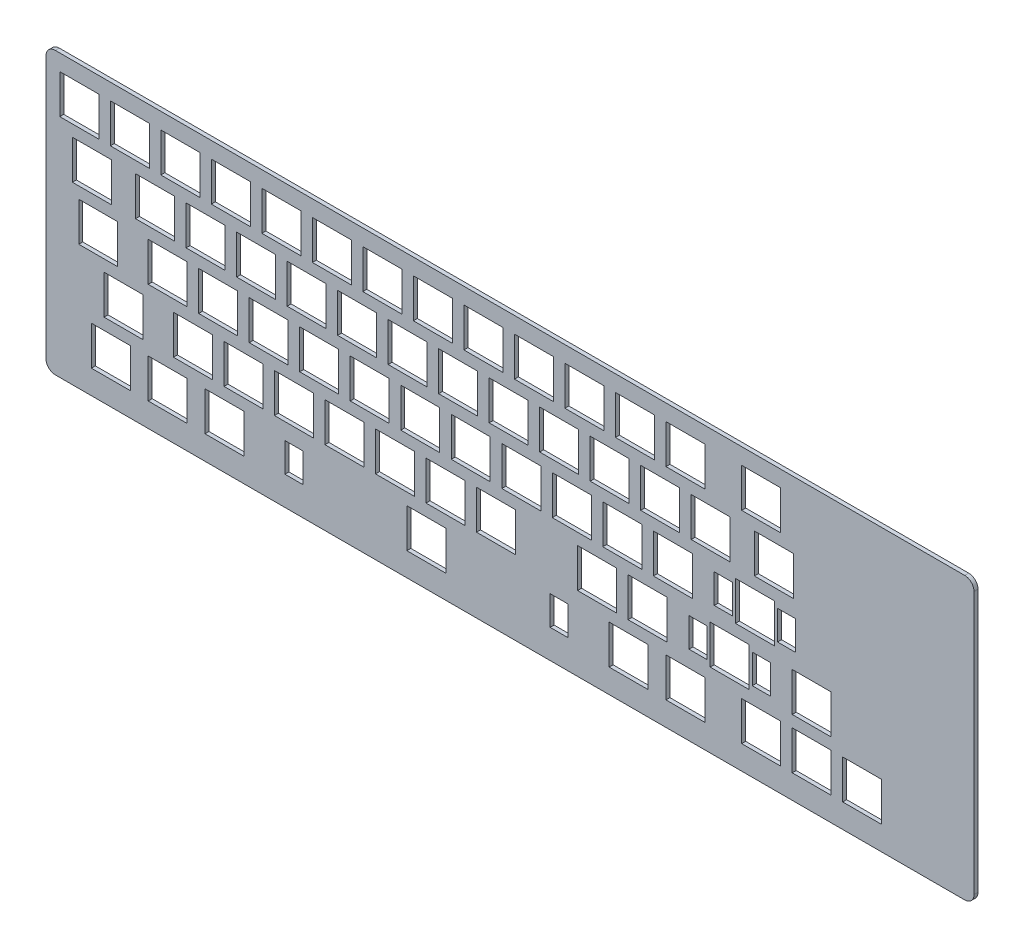
SolidWorks part; units mm, degrees
ref_plane "Front Plane" through (0, 0, 0) normal (0, 0, 1) x (1, 0, 0)
ref_plane "Top Plane" through (0, 0, 0) normal (0, 1, 0) x (1, 0, 0)
ref_plane "Right Plane" through (0, 0, 0) normal (1, 0, 0) x (0, 0, -1)
sketch "plate" plane through (0, 0, 5.0925) normal (0, 0, 1) x (1, 0, 0)
  line L11 (33.52, -25.21) -> (376.52, -25.21)
  line L13 (380.02, -28.71) -> (380.02, -127.71)
  line L15 (376.52, -131.21) -> (33.52, -131.21)
  line L17 (30.02, -127.71) -> (30.02, -28.71)
  line L18 (380.02, -130.71) -> (380.02, -26.71) construction
  arc A14 (33.52, -131.21) -> (30.02, -127.71) centre (33.52, -127.71) cw
  arc A15 (30.02, -28.71) -> (33.52, -25.21) centre (33.52, -28.71) cw
  arc A16 (380.02, -127.71) -> (376.52, -131.21) centre (376.52, -127.71) cw
  arc A17 (380.02, -28.71) -> (376.52, -25.21) centre (376.52, -28.71) ccw
  dimension "D1" = 0
  dimension "D2" = 343
  dimension "D3" = 343
extrude "Boss-Extrude1" add sketch "plate" against normal blind 1.5
sketch "keyholes" plane through (0, 0, 5.0925) normal (0, 0, 1) x (1, 0, 0)
  line L0 (140.003, -65.0623) -> (154.7028, -65.0623) construction
  line L1 (35.228, -31.312) -> (49.9278, -31.312)
  line L2 (35.228, -31.312) -> (35.228, -46.0123)
  line L3 (35.228, -46.0123) -> (49.9278, -46.0123)
  line L4 (49.9278, -31.312) -> (49.9278, -46.0123)
  line L5 (54.278, -31.312) -> (68.9778, -31.312)
  line L6 (54.278, -31.312) -> (54.278, -46.0123)
  line L7 (54.278, -46.0123) -> (68.9778, -46.0123)
  line L8 (68.9778, -31.312) -> (68.9778, -46.0123)
  line L9 (73.328, -31.312) -> (88.0278, -31.312)
  line L10 (73.328, -31.312) -> (73.328, -46.0123)
  line L11 (73.328, -46.0123) -> (88.0278, -46.0123)
  line L12 (88.0278, -31.312) -> (88.0278, -46.0123)
  line L13 (92.378, -31.312) -> (107.0778, -31.312)
  line L14 (92.378, -31.312) -> (92.378, -46.0123)
  line L15 (92.378, -46.0123) -> (107.0778, -46.0123)
  line L16 (107.0778, -31.312) -> (107.0778, -46.0123)
  line L17 (111.428, -31.312) -> (126.1278, -31.312)
  line L18 (111.428, -31.312) -> (111.428, -46.0123)
  line L19 (111.428, -46.0123) -> (126.1278, -46.0123)
  line L20 (126.1278, -31.312) -> (126.1278, -46.0123)
  line L21 (130.478, -31.312) -> (145.1778, -31.312)
  line L22 (130.478, -31.312) -> (130.478, -46.0123)
  line L23 (130.478, -46.0123) -> (145.1778, -46.0123)
  line L24 (145.1778, -31.312) -> (145.1778, -46.0123)
  line L25 (149.528, -31.312) -> (164.2278, -31.312)
  line L26 (149.528, -31.312) -> (149.528, -46.0123)
  line L27 (149.528, -46.0123) -> (164.2278, -46.0123)
  line L28 (164.2278, -31.312) -> (164.2278, -46.0123)
  line L29 (168.578, -31.312) -> (183.2778, -31.312)
  line L30 (168.578, -31.312) -> (168.578, -46.0123)
  line L31 (168.578, -46.0123) -> (183.2778, -46.0123)
  line L32 (183.2778, -31.312) -> (183.2778, -46.0123)
  line L33 (187.628, -31.312) -> (202.3278, -31.312)
  line L34 (187.628, -31.312) -> (187.628, -46.0123)
  line L35 (187.628, -46.0123) -> (202.3278, -46.0123)
  line L36 (202.3278, -31.312) -> (202.3278, -46.0123)
  line L37 (206.678, -31.312) -> (221.3778, -31.312)
  line L38 (206.678, -31.312) -> (206.678, -46.0123)
  line L39 (206.678, -46.0123) -> (221.3778, -46.0123)
  line L40 (221.3778, -31.312) -> (221.3778, -46.0123)
  line L41 (225.728, -31.312) -> (240.4278, -31.312)
  line L42 (225.728, -31.312) -> (225.728, -46.0123)
  line L43 (225.728, -46.0123) -> (240.4278, -46.0123)
  line L44 (240.4278, -31.312) -> (240.4278, -46.0123)
  line L45 (244.778, -31.312) -> (259.4778, -31.312)
  line L46 (244.778, -31.312) -> (244.778, -46.0123)
  line L47 (244.778, -46.0123) -> (259.4778, -46.0123)
  line L48 (259.4778, -31.312) -> (259.4778, -46.0123)
  line L53 (292.403, -31.312) -> (307.1028, -31.312)
  line L54 (292.403, -31.312) -> (292.403, -46.0123)
  line L55 (292.403, -46.0123) -> (307.1028, -46.0123)
  line L56 (307.1028, -31.312) -> (307.1028, -46.0123)
  line L57 (39.9905, -50.362) -> (54.6903, -50.362)
  line L58 (39.9905, -50.362) -> (39.9905, -65.0623)
  line L59 (39.9905, -65.0623) -> (54.6903, -65.0623)
  line L60 (54.6903, -50.362) -> (54.6903, -65.0623)
  line L61 (63.803, -50.362) -> (78.5028, -50.362)
  line L62 (63.803, -50.362) -> (63.803, -65.0623)
  line L63 (63.803, -65.0623) -> (78.5028, -65.0623)
  line L64 (78.5028, -50.362) -> (78.5028, -65.0623)
  line L65 (82.853, -50.362) -> (97.5528, -50.362)
  line L66 (82.853, -50.362) -> (82.853, -65.0623)
  line L67 (82.853, -65.0623) -> (97.5528, -65.0623)
  line L68 (97.5528, -50.362) -> (97.5528, -65.0623)
  line L69 (101.903, -50.362) -> (116.6028, -50.362)
  line L70 (101.903, -50.362) -> (101.903, -65.0623)
  line L71 (101.903, -65.0623) -> (116.6028, -65.0623)
  line L72 (116.6028, -50.362) -> (116.6028, -65.0623)
  line L77 (140.003, -50.362) -> (154.7028, -50.362)
  line L78 (140.003, -50.362) -> (140.003, -65.0623)
  line L79 (140.003, -65.0623) -> (154.7028, -65.0623)
  line L80 (154.7028, -50.362) -> (154.7028, -65.0623)
  line L81 (159.053, -65.0623) -> (173.7528, -65.0623) construction
  line L82 (159.053, -50.362) -> (173.7528, -50.362)
  line L83 (159.053, -50.362) -> (159.053, -65.0623)
  line L84 (159.053, -65.0623) -> (173.7528, -65.0623)
  line L85 (173.7528, -50.362) -> (173.7528, -65.0623)
  line L86 (178.103, -65.0623) -> (192.8028, -65.0623) construction
  line L87 (178.103, -50.362) -> (192.8028, -50.362)
  line L88 (178.103, -50.362) -> (178.103, -65.0623)
  line L89 (178.103, -65.0623) -> (192.8028, -65.0623)
  line L90 (192.8028, -50.362) -> (192.8028, -65.0623)
  line L91 (121.3653, -84.1123) -> (121.3653, -69.412) construction
  line L92 (106.6655, -69.412) -> (121.3653, -69.412)
  line L93 (106.6655, -69.412) -> (106.6655, -84.1123)
  line L94 (106.6655, -84.1123) -> (121.3653, -84.1123)
  line L95 (121.3653, -69.412) -> (121.3653, -84.1123)
  line L96 (144.7655, -84.1123) -> (159.4653, -84.1123) construction
  line L97 (125.7155, -69.412) -> (140.4153, -69.412)
  line L98 (125.7155, -69.412) -> (125.7155, -84.1123)
  line L99 (125.7155, -84.1123) -> (140.4153, -84.1123)
  line L100 (140.4153, -69.412) -> (140.4153, -84.1123)
  line L101 (144.7655, -69.412) -> (159.4653, -69.412)
  line L102 (144.7655, -69.412) -> (144.7655, -84.1123)
  line L103 (144.7655, -84.1123) -> (159.4653, -84.1123)
  line L104 (159.4653, -69.412) -> (159.4653, -84.1123)
  line L106 (163.8155, -69.412) -> (178.5153, -69.412)
  line L107 (163.8155, -69.412) -> (163.8155, -84.1123)
  line L108 (163.8155, -84.1123) -> (178.5153, -84.1123)
  line L109 (178.5153, -69.412) -> (178.5153, -84.1123)
  line L110 (182.8655, -69.412) -> (197.5653, -69.412)
  line L111 (182.8655, -69.412) -> (182.8655, -84.1123)
  line L112 (182.8655, -84.1123) -> (197.5653, -84.1123)
  line L113 (197.5653, -69.412) -> (197.5653, -84.1123)
  line L114 (42.3717, -69.412) -> (57.0716, -69.412)
  line L115 (42.3717, -69.412) -> (42.3717, -84.1123)
  line L116 (42.3717, -84.1123) -> (57.0716, -84.1123)
  line L117 (57.0716, -69.412) -> (57.0716, -84.1123)
  line L118 (68.5655, -69.412) -> (83.2653, -69.412)
  line L119 (68.5655, -69.412) -> (68.5655, -84.1123)
  line L120 (68.5655, -84.1123) -> (83.2653, -84.1123)
  line L121 (83.2653, -69.412) -> (83.2653, -84.1123)
  line L122 (87.6155, -69.412) -> (102.3153, -69.412)
  line L123 (87.6155, -69.412) -> (87.6155, -84.1123)
  line L124 (87.6155, -84.1123) -> (102.3153, -84.1123)
  line L125 (102.3153, -69.412) -> (102.3153, -84.1123)
  line L130 (197.153, -50.362) -> (211.8528, -50.362)
  line L131 (197.153, -50.362) -> (197.153, -65.0623)
  line L132 (197.153, -65.0623) -> (211.8528, -65.0623)
  line L133 (211.8528, -50.362) -> (211.8528, -65.0623)
  line L134 (201.9155, -69.412) -> (216.6153, -69.412)
  line L135 (201.9155, -69.412) -> (201.9155, -84.1123)
  line L136 (201.9155, -84.1123) -> (216.6153, -84.1123)
  line L137 (216.6153, -69.412) -> (216.6153, -84.1123)
  line L138 (216.203, -50.362) -> (230.9028, -50.362)
  line L139 (216.203, -50.362) -> (216.203, -65.0623)
  line L140 (216.203, -65.0623) -> (230.9028, -65.0623)
  line L141 (230.9028, -50.362) -> (230.9028, -65.0623)
  line L142 (220.9655, -69.412) -> (235.6653, -69.412)
  line L143 (220.9655, -69.412) -> (220.9655, -84.1123)
  line L144 (220.9655, -84.1123) -> (235.6653, -84.1123)
  line L145 (235.6653, -69.412) -> (235.6653, -84.1123)
  line L146 (235.253, -50.362) -> (249.9528, -50.362)
  line L147 (235.253, -50.362) -> (235.253, -65.0623)
  line L148 (235.253, -65.0623) -> (249.9528, -65.0623)
  line L149 (249.9528, -50.362) -> (249.9528, -65.0623)
  line L150 (254.303, -50.362) -> (269.0028, -50.362)
  line L151 (254.303, -50.362) -> (254.303, -65.0623)
  line L152 (254.303, -65.0623) -> (269.0028, -65.0623)
  line L153 (269.0028, -50.362) -> (269.0028, -65.0623)
  line L154 (240.0155, -69.412) -> (254.7153, -69.412)
  line L155 (240.0155, -69.412) -> (240.0155, -84.1123)
  line L156 (240.0155, -84.1123) -> (254.7153, -84.1123)
  line L157 (254.7153, -69.412) -> (254.7153, -84.1123)
  line L158 (259.0655, -69.412) -> (273.7653, -69.412)
  line L159 (259.0655, -69.412) -> (259.0655, -84.1123)
  line L160 (259.0655, -84.1123) -> (273.7653, -84.1123)
  line L161 (273.7653, -69.412) -> (273.7653, -84.1123)
  line L162 (273.353, -50.362) -> (288.0528, -50.362)
  line L163 (273.353, -50.362) -> (273.353, -65.0623)
  line L164 (273.353, -65.0623) -> (288.0528, -65.0623)
  line L165 (288.0528, -50.362) -> (288.0528, -65.0623)
  line L166 (297.1655, -50.362) -> (311.8653, -50.362)
  line L167 (297.1655, -50.362) -> (297.1655, -65.0623)
  line L168 (297.1655, -65.0623) -> (311.8653, -65.0623)
  line L169 (311.8653, -50.362) -> (311.8653, -65.0623)
  line L170 (290.0217, -69.412) -> (304.7216, -69.412)
  line L171 (290.0217, -69.412) -> (290.0217, -84.1123)
  line L172 (290.0217, -84.1123) -> (304.7216, -84.1123)
  line L173 (304.7216, -69.412) -> (304.7216, -84.1123)
  line L174 (282.0387, -71.255) -> (288.8388, -71.255)
  line L175 (282.0387, -71.255) -> (282.0387, -82.255)
  line L176 (282.0387, -82.255) -> (288.8388, -82.255)
  line L177 (288.8388, -71.255) -> (288.8388, -82.255)
  line L178 (305.9188, -71.255) -> (312.7188, -71.255)
  line L179 (305.9188, -71.255) -> (305.9188, -82.255)
  line L180 (305.9188, -82.255) -> (312.7188, -82.255)
  line L181 (312.7188, -71.255) -> (312.7188, -82.255)
  line L182 (330.503, -107.512) -> (345.2028, -107.512)
  line L183 (330.503, -107.512) -> (330.503, -122.2123)
  line L184 (330.503, -122.2123) -> (345.2028, -122.2123)
  line L185 (345.2028, -107.512) -> (345.2028, -122.2123)
  line L186 (311.453, -107.512) -> (326.1528, -107.512)
  line L187 (311.453, -107.512) -> (311.453, -122.2123)
  line L188 (311.453, -122.2123) -> (326.1528, -122.2123)
  line L189 (326.1528, -107.512) -> (326.1528, -122.2123)
  line L190 (292.403, -107.512) -> (307.1028, -107.512)
  line L191 (292.403, -107.512) -> (292.403, -122.2123)
  line L192 (292.403, -122.2123) -> (307.1028, -122.2123)
  line L193 (307.1028, -107.512) -> (307.1028, -122.2123)
  line L194 (311.453, -88.462) -> (326.1528, -88.462)
  line L195 (311.453, -88.462) -> (311.453, -103.1623)
  line L196 (311.453, -103.1623) -> (326.1528, -103.1623)
  line L197 (326.1528, -88.462) -> (326.1528, -103.1623)
  line L198 (280.4967, -88.462) -> (295.1966, -88.462)
  line L199 (280.4967, -88.462) -> (280.4967, -103.1623)
  line L200 (280.4967, -103.1623) -> (295.1966, -103.1623)
  line L201 (295.1966, -88.462) -> (295.1966, -103.1623)
  line L202 (296.3938, -90.305) -> (303.1938, -90.305)
  line L203 (296.3938, -90.305) -> (296.3938, -101.305)
  line L204 (296.3938, -101.305) -> (303.1938, -101.305)
  line L205 (303.1938, -90.305) -> (303.1938, -101.305)
  line L206 (272.5138, -90.305) -> (279.3138, -90.305)
  line L207 (272.5138, -90.305) -> (272.5138, -101.305)
  line L208 (272.5138, -101.305) -> (279.3138, -101.305)
  line L209 (279.3138, -90.305) -> (279.3138, -101.305)
  line L210 (263.828, -107.512) -> (278.5278, -107.512)
  line L211 (263.828, -107.512) -> (263.828, -122.2123)
  line L212 (263.828, -122.2123) -> (278.5278, -122.2123)
  line L213 (278.5278, -107.512) -> (278.5278, -122.2123)
  line L214 (242.3967, -107.512) -> (257.0966, -107.512)
  line L215 (242.3967, -107.512) -> (242.3967, -122.2123)
  line L216 (242.3967, -122.2123) -> (257.0966, -122.2123)
  line L217 (257.0966, -107.512) -> (257.0966, -122.2123)
  line L218 (249.5405, -88.462) -> (264.2403, -88.462)
  line L219 (249.5405, -88.462) -> (249.5405, -103.1623)
  line L220 (249.5405, -103.1623) -> (264.2403, -103.1623)
  line L221 (264.2403, -88.462) -> (264.2403, -103.1623)
  line L222 (230.4905, -88.462) -> (245.1903, -88.462)
  line L223 (230.4905, -88.462) -> (230.4905, -103.1623)
  line L224 (230.4905, -103.1623) -> (245.1903, -103.1623)
  line L225 (245.1903, -88.462) -> (245.1903, -103.1623)
  line L226 (220.1538, -109.355) -> (226.9538, -109.355)
  line L227 (220.1538, -109.355) -> (220.1538, -120.355)
  line L228 (220.1538, -120.355) -> (226.9538, -120.355)
  line L229 (226.9538, -109.355) -> (226.9538, -120.355)
  line L230 (192.3905, -88.462) -> (207.0903, -88.462)
  line L231 (192.3905, -88.462) -> (192.3905, -103.1623)
  line L232 (192.3905, -103.1623) -> (207.0903, -103.1623)
  line L233 (207.0903, -88.462) -> (207.0903, -103.1623)
  line L234 (166.0967, -107.637) -> (180.7966, -107.637)
  line L235 (166.0967, -107.637) -> (166.0967, -122.3373)
  line L236 (166.0967, -122.3373) -> (180.7966, -122.3373)
  line L237 (180.7966, -107.637) -> (180.7966, -122.3373)
  line L238 (173.3405, -88.462) -> (188.0403, -88.462)
  line L239 (173.3405, -88.462) -> (173.3405, -103.1623)
  line L240 (173.3405, -103.1623) -> (188.0403, -103.1623)
  line L241 (188.0403, -88.462) -> (188.0403, -103.1623)
  line L242 (154.2905, -88.462) -> (168.9903, -88.462)
  line L243 (154.2905, -88.462) -> (154.2905, -103.1623)
  line L244 (154.2905, -103.1623) -> (168.9903, -103.1623)
  line L245 (168.9903, -88.462) -> (168.9903, -103.1623)
  line L246 (120.1538, -109.355) -> (126.9537, -109.355)
  line L247 (120.1538, -109.355) -> (120.1538, -120.355)
  line L248 (120.1538, -120.355) -> (126.9537, -120.355)
  line L249 (126.9537, -109.355) -> (126.9537, -120.355)
  line L250 (135.2405, -88.462) -> (149.9403, -88.462)
  line L251 (135.2405, -88.462) -> (135.2405, -103.1623)
  line L252 (135.2405, -103.1623) -> (149.9403, -103.1623)
  line L253 (149.9403, -88.462) -> (149.9403, -103.1623)
  line L254 (116.1905, -88.462) -> (130.8903, -88.462)
  line L255 (116.1905, -88.462) -> (116.1905, -103.1623)
  line L256 (116.1905, -103.1623) -> (130.8903, -103.1623)
  line L257 (130.8903, -88.462) -> (130.8903, -103.1623)
  line L258 (97.1405, -88.462) -> (111.8403, -88.462)
  line L259 (97.1405, -88.462) -> (97.1405, -103.1623)
  line L260 (97.1405, -103.1623) -> (111.8403, -103.1623)
  line L261 (111.8403, -88.462) -> (111.8403, -103.1623)
  line L262 (89.9967, -107.512) -> (104.6966, -107.512)
  line L263 (89.9967, -107.512) -> (89.9967, -122.2123)
  line L264 (89.9967, -122.2123) -> (104.6966, -122.2123)
  line L265 (104.6966, -107.512) -> (104.6966, -122.2123)
  line L266 (78.0905, -88.462) -> (92.7903, -88.462)
  line L267 (78.0905, -88.462) -> (78.0905, -103.1623)
  line L268 (78.0905, -103.1623) -> (92.7903, -103.1623)
  line L269 (92.7903, -88.462) -> (92.7903, -103.1623)
  line L270 (68.5655, -107.512) -> (83.2653, -107.512)
  line L271 (68.5655, -107.512) -> (68.5655, -122.2123)
  line L272 (68.5655, -122.2123) -> (83.2653, -122.2123)
  line L273 (83.2653, -107.512) -> (83.2653, -122.2123)
  line L274 (47.1342, -107.512) -> (61.8341, -107.512)
  line L275 (47.1342, -107.512) -> (47.1342, -122.2123)
  line L276 (47.1342, -122.2123) -> (61.8341, -122.2123)
  line L277 (61.8341, -107.512) -> (61.8341, -122.2123)
  line L278 (51.8967, -88.462) -> (66.5966, -88.462)
  line L279 (51.8967, -88.462) -> (51.8967, -103.1623)
  line L280 (51.8967, -103.1623) -> (66.5966, -103.1623)
  line L281 (66.5966, -88.462) -> (66.5966, -103.1623)
  line L282 (263.828, -31.312) -> (278.5278, -31.312)
  line L283 (263.828, -31.312) -> (263.828, -46.0123)
  line L284 (263.828, -46.0123) -> (278.5278, -46.0123)
  line L285 (278.5278, -31.312) -> (278.5278, -46.0123)
  line L286 (120.953, -50.362) -> (135.6528, -50.362)
  line L287 (120.953, -50.362) -> (120.953, -65.0623)
  line L288 (120.953, -65.0623) -> (135.6528, -65.0623)
  line L289 (135.6528, -50.362) -> (135.6528, -65.0623)
  spline S2 degree 1 poles (154.2689, -64.3835) (154.7028, -65.0623) knots 0 0 1 1 construction
  spline S3 degree 1 poles (173.3189, -64.3835) (173.7528, -65.0623) knots 0 0 1 1 construction
  spline S4 degree 1 poles (192.3689, -64.3835) (192.8028, -65.0623) knots 0 0 1 1 construction
  spline S5 degree 1 poles (120.9314, -83.4335) (121.3653, -84.1123) knots 0 0 1 1 construction
  spline S6 degree 1 poles (159.0314, -83.4335) (159.4653, -84.1123) knots 0 0 1 1 construction
extrude "Cut-Extrude2" cut sketch "keyholes" against normal blind 3.6
